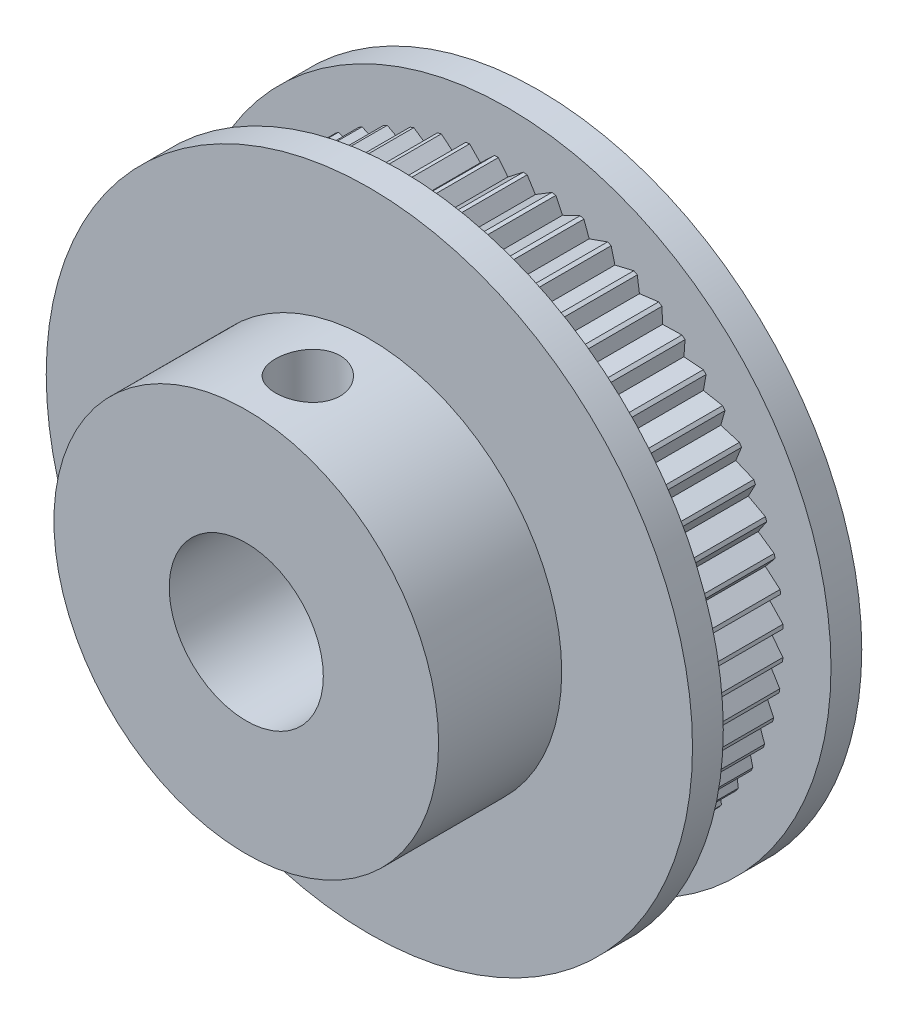
SolidWorks part; units mm, degrees
ref_plane "Front Plane" through (0, 0, 0) normal (0, 0, 1) x (1, 0, 0)
ref_plane "Top Plane" through (0, 0, 0) normal (0, 1, 0) x (1, 0, 0)
ref_plane "Right Plane" through (0, 0, 0) normal (1, 0, 0) x (0, 0, -1)
sketch "Sketch1" plane through (0, 0, 0) normal (0, 0, 1) x (1, 0, 0)
  circle A0 centre (0, 0) radius 21
extrude "Boss-Extrude1" add sketch "Sketch1" along normal blind 11
sketch "Sketch2" plane through (0, 0, 11) normal (0, 0, 1) x (1, 0, 0)
  circle A0 centre (0, 0) radius 12.5
extrude "Boss-Extrude2" add sketch "Sketch2" along normal blind 8
sketch "Sketch3" plane through (0, 0, 19) normal (0, 0, 1) x (1, 0, 0)
  circle A0 centre (0, 0) radius 5.0075
  dimension "D1" = 10.015
extrude "Cut-Extrude1" cut sketch "Sketch3" against normal blind 20
sketch "Sketch4" plane through (0, 0, 11) normal (0, 0, 1) x (1, 0, 0)
  line L0 (0, 0) -> (0, 18) construction
  line L1 (0, 18) -> (1.1673, 18) construction
  line L7 (0, 17.1038) -> (1.1673, 18)
  line L8 (1.1673, 18) -> (-0.7037, 18)
  line L9 (-0.7037, 18) -> (0, 17.1038)
  line L10 (1.7878, 17.0101) -> (3.0424, 17.7794)
  line L11 (3.0424, 17.7794) -> (1.1816, 17.975)
  line L12 (1.1816, 17.975) -> (1.7878, 17.0101)
  line L13 (3.5561, 16.7301) -> (4.8842, 17.364)
  line L14 (4.8842, 17.364) -> (3.0541, 17.753)
  line L15 (3.0541, 17.753) -> (3.5561, 16.7301)
  line L16 (5.2854, 16.2667) -> (6.6725, 16.7583)
  line L17 (6.6725, 16.7583) -> (4.893, 17.3365)
  line L18 (4.893, 17.3365) -> (5.2854, 16.2667)
  line L19 (6.9568, 15.6251) -> (8.3876, 15.969)
  line L20 (8.3876, 15.969) -> (6.6784, 16.7301)
  line L21 (6.6784, 16.7301) -> (6.9568, 15.6251)
  line L22 (8.5519, 14.8124) -> (10.0109, 15.0048)
  line L23 (10.0109, 15.0048) -> (8.3906, 15.9403)
  line L24 (8.3906, 15.9403) -> (8.5519, 14.8124)
  line L25 (10.0534, 13.8373) -> (11.5245, 13.8762)
  line L26 (11.5245, 13.8762) -> (10.0108, 14.9759)
  line L27 (10.0108, 14.9759) -> (10.0534, 13.8373)
  line L28 (11.4447, 12.7106) -> (12.9118, 12.5955)
  line L29 (12.9118, 12.5955) -> (11.5214, 13.8475)
  line L30 (11.5214, 13.8475) -> (11.4447, 12.7106)
  line L31 (12.7106, 11.4447) -> (14.1577, 11.1769)
  line L32 (14.1577, 11.1769) -> (12.9057, 12.5673)
  line L33 (12.9057, 12.5673) -> (12.7106, 11.4447)
  line L34 (13.8373, 10.0534) -> (15.2484, 9.6358)
  line L35 (15.2484, 9.6358) -> (14.1487, 11.1495)
  line L36 (14.1487, 11.1495) -> (13.8373, 10.0534)
  line L37 (14.8124, 8.5519) -> (16.1721, 7.9891)
  line L38 (16.1721, 7.9891) -> (15.2366, 9.6094)
  line L39 (15.2366, 9.6094) -> (14.8124, 8.5519)
  line L40 (15.6251, 6.9568) -> (16.9186, 6.2549)
  line L41 (16.9186, 6.2549) -> (16.1576, 7.9641)
  line L42 (16.1576, 7.9641) -> (15.6251, 6.9568)
  line L43 (16.2667, 5.2854) -> (17.4797, 4.4521)
  line L44 (17.4797, 4.4521) -> (16.9016, 6.2316)
  line L45 (16.9016, 6.2316) -> (16.2667, 5.2854)
  line L46 (16.7301, 3.5561) -> (17.8494, 2.6006)
  line L47 (17.8494, 2.6006) -> (17.4603, 4.4308)
  line L48 (17.4603, 4.4308) -> (16.7301, 3.5561)
  line L49 (17.0101, 1.7878) -> (18.0234, 0.7206)
  line L50 (18.0234, 0.7206) -> (17.8278, 2.5814)
  line L51 (17.8278, 2.5814) -> (17.0101, 1.7878)
  line L52 (17.1038, 0) -> (18, -1.1673)
  line L53 (18, -1.1673) -> (18, 0.7037)
  line L54 (18, 0.7037) -> (17.1038, 0)
  line L55 (17.0101, -1.7878) -> (17.7794, -3.0424)
  line L56 (17.7794, -3.0424) -> (17.975, -1.1816)
  line L57 (17.975, -1.1816) -> (17.0101, -1.7878)
  line L58 (16.7301, -3.5561) -> (17.364, -4.8842)
  line L59 (17.364, -4.8842) -> (17.753, -3.0541)
  line L60 (17.753, -3.0541) -> (16.7301, -3.5561)
  line L61 (16.2667, -5.2854) -> (16.7583, -6.6725)
  line L62 (16.7583, -6.6725) -> (17.3365, -4.893)
  line L63 (17.3365, -4.893) -> (16.2667, -5.2854)
  line L64 (15.6251, -6.9568) -> (15.969, -8.3876)
  line L65 (15.969, -8.3876) -> (16.7301, -6.6784)
  line L66 (16.7301, -6.6784) -> (15.6251, -6.9568)
  line L67 (14.8124, -8.5519) -> (15.0048, -10.0109)
  line L68 (15.0048, -10.0109) -> (15.9403, -8.3906)
  line L69 (15.9403, -8.3906) -> (14.8124, -8.5519)
  line L70 (13.8373, -10.0534) -> (13.8762, -11.5245)
  line L71 (13.8762, -11.5245) -> (14.9759, -10.0108)
  line L72 (14.9759, -10.0108) -> (13.8373, -10.0534)
  line L73 (12.7106, -11.4447) -> (12.5955, -12.9118)
  line L74 (12.5955, -12.9118) -> (13.8475, -11.5214)
  line L75 (13.8475, -11.5214) -> (12.7106, -11.4447)
  line L76 (11.4447, -12.7106) -> (11.1769, -14.1577)
  line L77 (11.1769, -14.1577) -> (12.5673, -12.9057)
  line L78 (12.5673, -12.9057) -> (11.4447, -12.7106)
  line L79 (10.0534, -13.8373) -> (9.6358, -15.2484)
  line L80 (9.6358, -15.2484) -> (11.1495, -14.1487)
  line L81 (11.1495, -14.1487) -> (10.0534, -13.8373)
  line L82 (8.5519, -14.8124) -> (7.9891, -16.1721)
  line L83 (7.9891, -16.1721) -> (9.6094, -15.2366)
  line L84 (9.6094, -15.2366) -> (8.5519, -14.8124)
  line L85 (6.9568, -15.6251) -> (6.2549, -16.9186)
  line L86 (6.2549, -16.9186) -> (7.9641, -16.1576)
  line L87 (7.9641, -16.1576) -> (6.9568, -15.6251)
  line L88 (5.2854, -16.2667) -> (4.4521, -17.4797)
  line L89 (4.4521, -17.4797) -> (6.2316, -16.9016)
  line L90 (6.2316, -16.9016) -> (5.2854, -16.2667)
  line L91 (3.5561, -16.7301) -> (2.6006, -17.8494)
  line L92 (2.6006, -17.8494) -> (4.4308, -17.4603)
  line L93 (4.4308, -17.4603) -> (3.5561, -16.7301)
  line L94 (1.7878, -17.0101) -> (0.7206, -18.0234)
  line L95 (0.7206, -18.0234) -> (2.5814, -17.8278)
  line L96 (2.5814, -17.8278) -> (1.7878, -17.0101)
  line L97 (0, -17.1038) -> (-1.1673, -18)
  line L98 (-1.1673, -18) -> (0.7037, -18)
  line L99 (0.7037, -18) -> (0, -17.1038)
  line L100 (-1.7878, -17.0101) -> (-3.0424, -17.7794)
  line L101 (-3.0424, -17.7794) -> (-1.1816, -17.975)
  line L102 (-1.1816, -17.975) -> (-1.7878, -17.0101)
  line L103 (-3.5561, -16.7301) -> (-4.8842, -17.364)
  line L104 (-4.8842, -17.364) -> (-3.0541, -17.753)
  line L105 (-3.0541, -17.753) -> (-3.5561, -16.7301)
  line L106 (-5.2854, -16.2667) -> (-6.6725, -16.7583)
  line L107 (-6.6725, -16.7583) -> (-4.893, -17.3365)
  line L108 (-4.893, -17.3365) -> (-5.2854, -16.2667)
  line L109 (-6.9568, -15.6251) -> (-8.3876, -15.969)
  line L110 (-8.3876, -15.969) -> (-6.6784, -16.7301)
  line L111 (-6.6784, -16.7301) -> (-6.9568, -15.6251)
  line L112 (-8.5519, -14.8124) -> (-10.0109, -15.0048)
  line L113 (-10.0109, -15.0048) -> (-8.3906, -15.9403)
  line L114 (-8.3906, -15.9403) -> (-8.5519, -14.8124)
  line L115 (-10.0534, -13.8373) -> (-11.5245, -13.8762)
  line L116 (-11.5245, -13.8762) -> (-10.0108, -14.9759)
  line L117 (-10.0108, -14.9759) -> (-10.0534, -13.8373)
  line L118 (-11.4447, -12.7106) -> (-12.9118, -12.5955)
  line L119 (-12.9118, -12.5955) -> (-11.5214, -13.8475)
  line L120 (-11.5214, -13.8475) -> (-11.4447, -12.7106)
  line L121 (-12.7106, -11.4447) -> (-14.1577, -11.1769)
  line L122 (-14.1577, -11.1769) -> (-12.9057, -12.5673)
  line L123 (-12.9057, -12.5673) -> (-12.7106, -11.4447)
  line L124 (-13.8373, -10.0534) -> (-15.2484, -9.6358)
  line L125 (-15.2484, -9.6358) -> (-14.1487, -11.1495)
  line L126 (-14.1487, -11.1495) -> (-13.8373, -10.0534)
  line L127 (-14.8124, -8.5519) -> (-16.1721, -7.9891)
  line L128 (-16.1721, -7.9891) -> (-15.2366, -9.6094)
  line L129 (-15.2366, -9.6094) -> (-14.8124, -8.5519)
  line L130 (-15.6251, -6.9568) -> (-16.9186, -6.2549)
  line L131 (-16.9186, -6.2549) -> (-16.1576, -7.9641)
  line L132 (-16.1576, -7.9641) -> (-15.6251, -6.9568)
  line L133 (-16.2667, -5.2854) -> (-17.4797, -4.4521)
  line L134 (-17.4797, -4.4521) -> (-16.9016, -6.2316)
  line L135 (-16.9016, -6.2316) -> (-16.2667, -5.2854)
  line L136 (-16.7301, -3.5561) -> (-17.8494, -2.6006)
  line L137 (-17.8494, -2.6006) -> (-17.4603, -4.4308)
  line L138 (-17.4603, -4.4308) -> (-16.7301, -3.5561)
  line L139 (-17.0101, -1.7878) -> (-18.0234, -0.7206)
  line L140 (-18.0234, -0.7206) -> (-17.8278, -2.5814)
  line L141 (-17.8278, -2.5814) -> (-17.0101, -1.7878)
  line L142 (-17.1038, 0) -> (-18, 1.1673)
  line L143 (-18, 1.1673) -> (-18, -0.7037)
  line L144 (-18, -0.7037) -> (-17.1038, 0)
  line L145 (-17.0101, 1.7878) -> (-17.7794, 3.0424)
  line L146 (-17.7794, 3.0424) -> (-17.975, 1.1816)
  line L147 (-17.975, 1.1816) -> (-17.0101, 1.7878)
  line L148 (-16.7301, 3.5561) -> (-17.364, 4.8842)
  line L149 (-17.364, 4.8842) -> (-17.753, 3.0541)
  line L150 (-17.753, 3.0541) -> (-16.7301, 3.5561)
  line L151 (-16.2667, 5.2854) -> (-16.7583, 6.6725)
  line L152 (-16.7583, 6.6725) -> (-17.3365, 4.893)
  line L153 (-17.3365, 4.893) -> (-16.2667, 5.2854)
  line L154 (-15.6251, 6.9568) -> (-15.969, 8.3876)
  line L155 (-15.969, 8.3876) -> (-16.7301, 6.6784)
  line L156 (-16.7301, 6.6784) -> (-15.6251, 6.9568)
  line L157 (-14.8124, 8.5519) -> (-15.0048, 10.0109)
  line L158 (-15.0048, 10.0109) -> (-15.9403, 8.3906)
  line L159 (-15.9403, 8.3906) -> (-14.8124, 8.5519)
  line L160 (-13.8373, 10.0534) -> (-13.8762, 11.5245)
  line L161 (-13.8762, 11.5245) -> (-14.9759, 10.0108)
  line L162 (-14.9759, 10.0108) -> (-13.8373, 10.0534)
  line L163 (-12.7106, 11.4447) -> (-12.5955, 12.9118)
  line L164 (-12.5955, 12.9118) -> (-13.8475, 11.5214)
  line L165 (-13.8475, 11.5214) -> (-12.7106, 11.4447)
  line L166 (-11.4447, 12.7106) -> (-11.1769, 14.1577)
  line L167 (-11.1769, 14.1577) -> (-12.5673, 12.9057)
  line L168 (-12.5673, 12.9057) -> (-11.4447, 12.7106)
  line L169 (-10.0534, 13.8373) -> (-9.6358, 15.2484)
  line L170 (-9.6358, 15.2484) -> (-11.1495, 14.1487)
  line L171 (-11.1495, 14.1487) -> (-10.0534, 13.8373)
  line L172 (-8.5519, 14.8124) -> (-7.9891, 16.1721)
  line L173 (-7.9891, 16.1721) -> (-9.6094, 15.2366)
  line L174 (-9.6094, 15.2366) -> (-8.5519, 14.8124)
  line L175 (-6.9568, 15.6251) -> (-6.2549, 16.9186)
  line L176 (-6.2549, 16.9186) -> (-7.9641, 16.1576)
  line L177 (-7.9641, 16.1576) -> (-6.9568, 15.6251)
  line L178 (-5.2854, 16.2667) -> (-4.4521, 17.4797)
  line L179 (-4.4521, 17.4797) -> (-6.2316, 16.9016)
  line L180 (-6.2316, 16.9016) -> (-5.2854, 16.2667)
  line L181 (-3.5561, 16.7301) -> (-2.6006, 17.8494)
  line L182 (-2.6006, 17.8494) -> (-4.4308, 17.4603)
  line L183 (-4.4308, 17.4603) -> (-3.5561, 16.7301)
  line L184 (-1.7878, 17.0101) -> (-0.7206, 18.0234)
  line L185 (-0.7206, 18.0234) -> (-2.5814, 17.8278)
  line L186 (-2.5814, 17.8278) -> (-1.7878, 17.0101)
  point P187 (0, 0)
  dimension "D1" = 60
extrude "Cut-Extrude5" cut sketch "Sketch4" against normal blind 7 from offset 2 offset against normal yes
sketch "Sketch5" plane through (0, 0, 11) normal (0, 0, 1) x (1, 0, 0)
  circle A0 centre (0, 0) radius 17.9
  circle A1 centre (0, 0) radius 21.0426
extrude "Cut-Extrude6" cut sketch "Sketch5" against normal blind 7 from offset 2 offset against normal yes
ref_plane "Plane2" through (0, 12.5, 0) normal (0, 1, 0) x (1, 0, 0)
hole_wizard "M5x0.8 Tapped Hole1" positions "Sketch10" profile "Sketch11" tap size "M5x0.8" standard "ANSI Metric"
sketch "Sketch10" plane through (0, 12.5, 0) normal (0, 1, 0) x (1, 0, 0)
  line L0 (0, -11) -> (0, -19) construction
  line L1 (-12.5, -11) -> (12.5, -11) construction
  line L2 (-12.5, -19) -> (12.5, -19) construction
  point P0 (0, -15)
  point P12 (0, -15)
sketch "Sketch11" plane through (0, 12.5, 15) normal (1, 0, 0) x (0, 0, 1)
  line L0 (0, 0) -> (0, 15.2618)
  line L1 (0, 15.2618) -> (2.1, 14)
  line L2 (2.1, 14) -> (2.1, 0)
  line L5 (2.1, 0) -> (0, 0)
  line L10 (0, 15.2618) -> (-2.1, 14) construction
  line L11 (0, -6.35) -> (0, 107.95) construction
  dimension "Tap Drill Dia." = 4.2
  dimension "Tap Drill Depth" = 14
  dimension "Drill Angle" = 118
